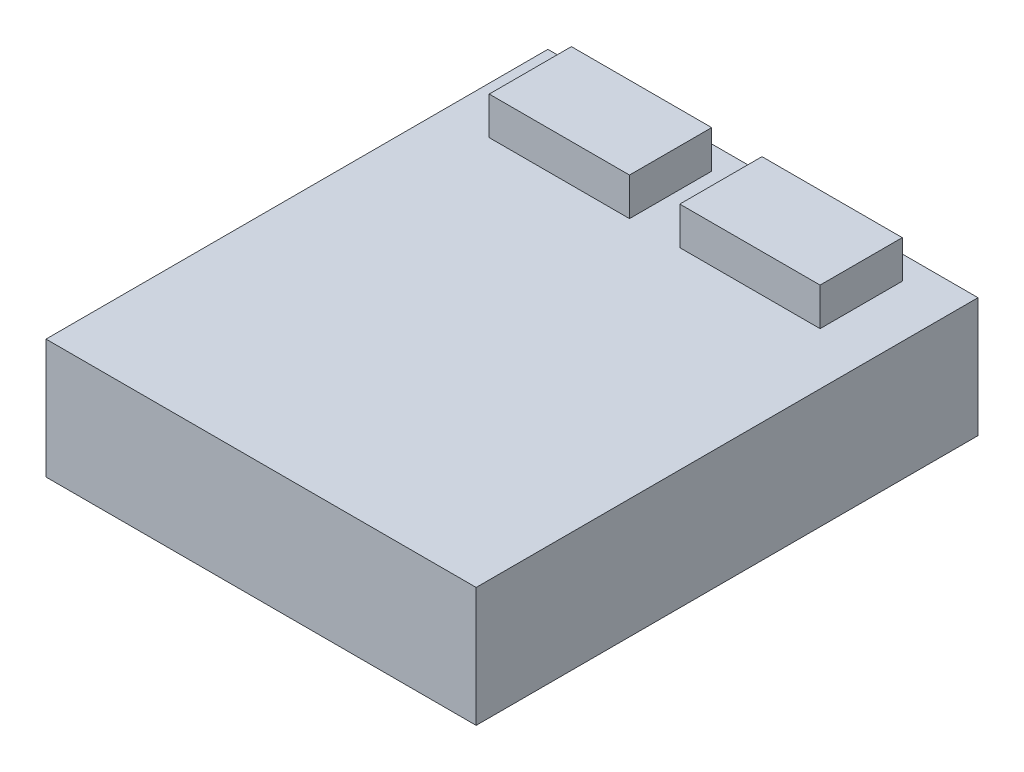
SolidWorks part; units mm, degrees
ref_plane "Спереди" through (0, 0, 0) normal (0, 0, 1) x (1, 0, 0)
ref_plane "Сверху" through (0, 0, 0) normal (0, 1, 0) x (1, 0, 0)
ref_plane "Справа" through (0, 0, 0) normal (1, 0, 0) x (0, 0, -1)
sketch "Эскиз1" plane through (0, 0, 0) normal (0, 1, 0) x (1, 0, 0)
  line L1 (0, 0) -> (1800, 0)
  line L2 (0, 0) -> (0, 2100)
  line L3 (0, 2100) -> (1800, 2100)
  line L4 (1800, 0) -> (1800, 2100)
  dimension "D1" = 2100
  dimension "D2" = 1800
extrude "Бобышка-Вытянуть1" add sketch "Эскиз1" along normal mid plane 500
sketch "Эскиз2" plane through (0, 250, 0) normal (0, 1, 0) x (1, 0, 0)
  line L1 (197.3813, 2001.2266) -> (784.3792, 2001.2266)
  line L2 (197.3813, 2001.2266) -> (197.3813, 1657.3288)
  line L3 (197.3813, 1657.3288) -> (784.3792, 1657.3288)
  line L4 (784.3792, 2001.2266) -> (784.3792, 1657.3288)
  line L5 (994.8684, 2001.2266) -> (1581.8663, 2001.2266)
  line L6 (994.8684, 2001.2266) -> (994.8684, 1657.3288)
  line L7 (994.8684, 1657.3288) -> (1581.8663, 1657.3288)
  line L8 (1581.8663, 2001.2266) -> (1581.8663, 1657.3288)
extrude "Бобышка-Вытянуть2" add sketch "Эскиз2" along normal blind 158
